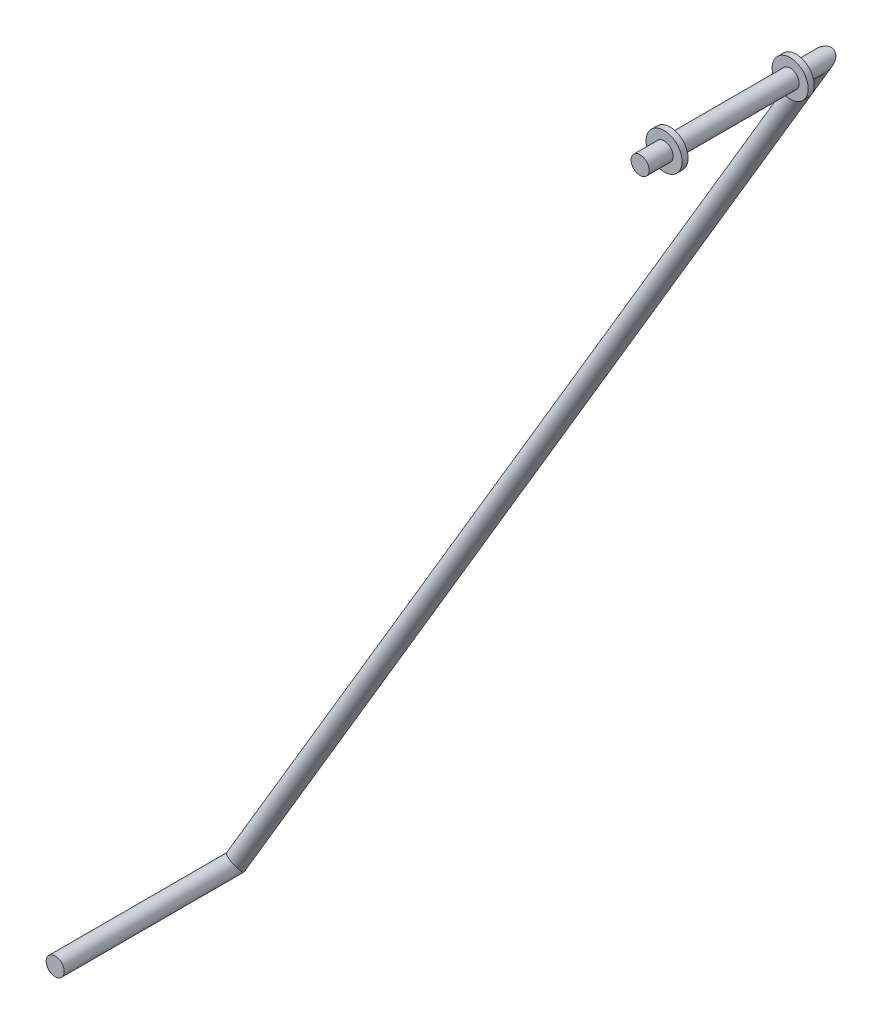
SolidWorks part; units mm, degrees
ref_plane "Plan de face" through (0, 0, 0) normal (0, 0, 1) x (1, 0, 0)
ref_plane "Plan de dessus" through (0, 0, 0) normal (0, 1, 0) x (1, 0, 0)
ref_plane "Plan de droite" through (0, 0, 0) normal (1, 0, 0) x (0, 0, -1)
sketch "Esquisse2" plane through (0, 0, 0) normal (0, 0, 1) x (1, 0, 0)
  line L0 (0, 0) -> (-97.4173, -164.2892)
  circle A0 centre (0, 0) radius 3 construction
  circle A1 centre (0, 0) radius 3
  circle A2 centre (-97.4173, -164.2892) radius 3
  dimension "D1" = 191.0002
ref_plane "Plan1" through (0, 0, 0) normal (0.8602, -0.51, 0) x (-0.51, -0.8602, 0)
sketch "Esquisse3" plane through (0, 0, 0) normal (0.8602, -0.51, 0) x (-0.51, -0.8602, 0)
  line L0 (0, -15) -> (0, 15)
  line L1 (0, 15) -> (191.0002, 15)
  line L2 (191.0002, 15) -> (191.0002, -15)
  dimension "D1" = 30
ref_plane "Plan2" through (0, 0, 15) normal (0, 0, -1) x (-1, 0, 0)
sketch "Esquisse4" plane through (0, 0, 15) normal (0, 0, -1) x (-1, 0, 0)
  circle A0 centre (0, 0) radius 1.5
  dimension "D1" = 3
sweep "Balayage1" add profiles "Esquisse4" path "Esquisse3"
sketch "Esquisse5" plane through (0, 0, 0) normal (0.8602, -0.51, 0) x (-0.51, -0.8602, 0)
  line L0 (-1.5, 16.5) -> (-1.5, -15) construction
  line L1 (-1.5, -10) -> (-3, -10)
  line L2 (-1.5, -10) -> (-1.5, -11)
  line L3 (-1.5, -11) -> (-3, -11)
  line L4 (-3, -10) -> (-3, -11)
  line L5 (0, 11) -> (0, -11) construction
  line L6 (-1.5, 11) -> (-3, 11)
  line L7 (-1.5, 11) -> (-1.5, 10)
  line L8 (-1.5, 10) -> (-3, 10)
  line L9 (-3, 11) -> (-3, 10)
  line L25 (3, 10) -> (-3, 10) construction
  line L26 (-3, -10) -> (3, -10) construction
  line L41 (-3, 10) -> (-3, -10) construction
  dimension "D1" = 1
revolve "Révolution1" add sketch "Esquisse5" angle 360 about L5
